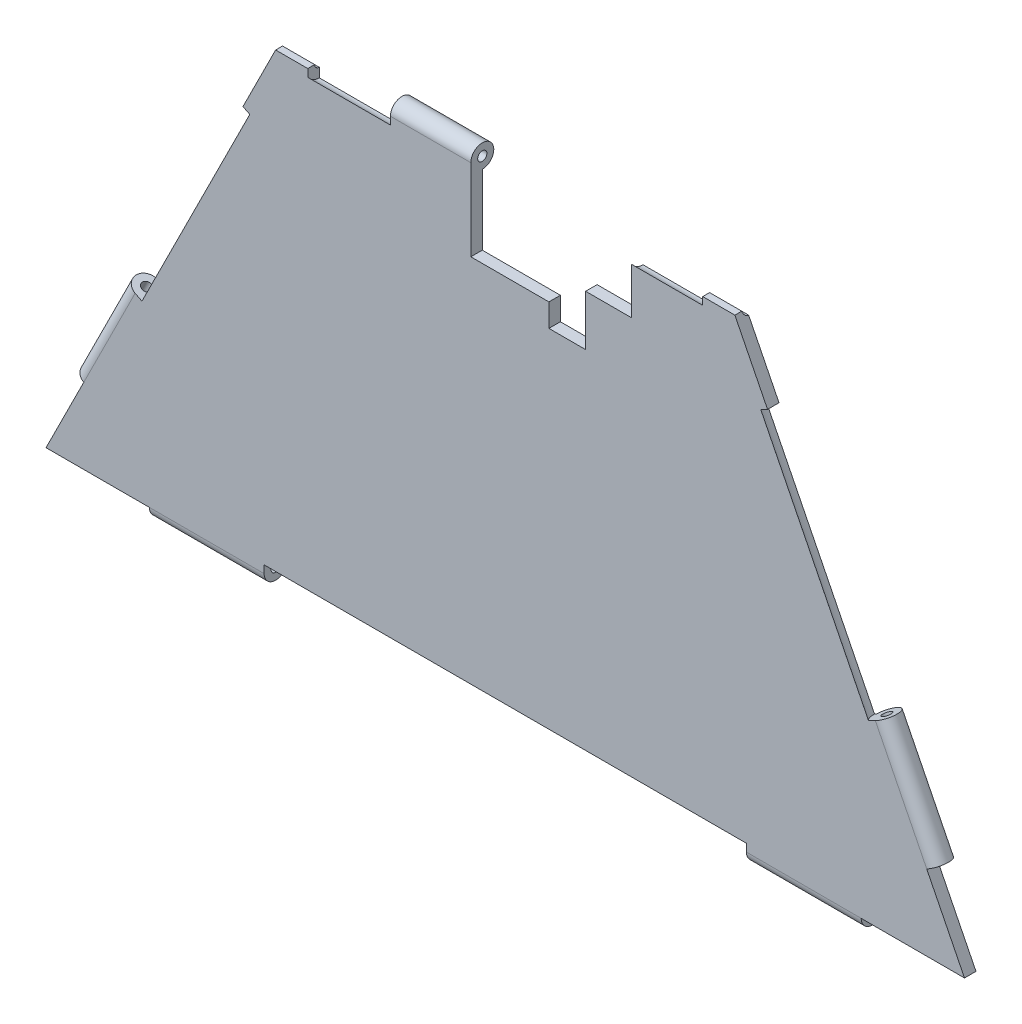
SolidWorks part; units mm, degrees
ref_plane "前视基准面" through (0, 0, 0) normal (0, 0, 1) x (1, 0, 0)
ref_plane "上视基准面" through (0, 0, 0) normal (0, 1, 0) x (1, 0, 0)
ref_plane "右视基准面" through (0, 0, 0) normal (1, 0, 0) x (0, 0, -1)
other "Configuration Table"
sketch "草图1" plane through (0, 0, 0) normal (0, 0, 1) x (1, 0, 0)
  line L0 (-200, 0) -> (-100, 200)
  line L1 (-100, 200) -> (100, 200)
  line L2 (100, 200) -> (200, 0)
  line L3 (200, 0) -> (-200, 0)
  dimension "D1" = 200
  dimension "D2" = 400
  dimension "D3" = 200
extrude "凸台-拉伸1" add sketch "草图1" along normal blind 5
sketch "草图3" plane through (0, 0, 0) normal (0, -1, 0) x (1, 0, 0)
  line L0 (-200, 2.5) -> (200, 2.5) construction
  line L1 (-155, 5) -> (-105, 5)
  line L2 (-155, 5) -> (-155, 0)
  line L3 (-155, 0) -> (-105, 0)
  line L4 (-200, 0) -> (200, 0)
  line L5 (200, 0) -> (200, 5)
  line L6 (200, 5) -> (-200, 5)
  line L7 (-200, 5) -> (-200, 0)
  line L8 (-200, 0) -> (200, 0)
  line L9 (200, 0) -> (200, 5)
  line L10 (200, 5) -> (-200, 5)
  line L11 (-200, 5) -> (-200, 0)
  line L12 (-105, 5) -> (-105, 0)
  line L13 (105, 5) -> (155, 5)
  line L14 (105, 5) -> (105, 0)
  line L15 (105, 0) -> (155, 0)
  line L16 (155, 5) -> (155, 0)
  line L17 (0, 5) -> (0, 0) construction
  dimension "D2" = 50
  dimension "D3" = 210
  dimension "D4" = 5
  dimension "D1" = 0
revolve "旋转5" add sketch "草图3" angle 360 about L3
sketch "草图6" plane through (-160, 80, 0) normal (-0.8944, 0.4472, 0) x (0, 0, 1)
  line L0 (2.5, 134.1641) -> (2.5, -89.4427) construction
  line L1 (5, 134.1641) -> (0, 134.1641) construction
  line L2 (5, -89.4427) -> (0, -89.4427) construction
  line L3 (0, 22.3607) -> (5, 22.3607) construction
  line L4 (0, 134.1641) -> (0, -89.4427) construction
  line L5 (5, 134.1641) -> (5, -89.4427) construction
  line L7 (0, -2.6393) -> (5, -2.6393)
  line L8 (0, -2.6393) -> (0, -52.6393)
  line L9 (0, -52.6393) -> (5, -52.6393)
  line L10 (5, -2.6393) -> (5, -52.6393)
  dimension "D1" = 50
  dimension "D2" = 5
  dimension "D3" = 25
sketch "草图7" plane through (0, 0, 0) normal (0, 0, -1) x (-1, 0, 0)
  line L1 (-50, 200) -> (50, 200)
  line L2 (-50, 200) -> (-50, 195)
  line L3 (-50, 195) -> (50, 195)
  line L4 (50, 200) -> (50, 195)
  line L6 (-100, 200) -> (100, 200) construction
  dimension "D1" = 100
  dimension "D2" = 5
  dimension "D3" = 50
revolve "旋转1" add sketch "草图7" angle 360 about L1
sketch "草图8" plane through (50, 0, 0) normal (1, 0, 0) x (0, 0, -1)
  circle A0 centre (0, 200) radius 2
  dimension "D1" = 4
extrude "切除-拉伸1" cut sketch "草图8" against normal through all both and the other way through all contours A0
revolve "旋转4" add sketch "草图6" angle 360 about L8
sketch "草图9" plane through (-23.541, -47.082, 0) normal (-0.4472, -0.8944, 0) x (0.8944, -0.4472, 0)
  circle A0 centre (-178.8854, 0) radius 2
  dimension "D1" = 4
extrude "切除-拉伸2" cut sketch "草图9" against normal up to surface (50 mm away) up to face at (-161.4891, 77.7937, -0.3452)
sketch "草图10" plane through (-1.1803, -2.3607, 0) normal (0.4472, 0.8944, 0) x (0.8944, -0.4472, 0)
  circle A0 centre (-178.8854, 0) radius 6
  dimension "D1" = 12
extrude "切除-拉伸3" cut sketch "草图10" along normal blind 105
sketch "草图11" plane through (-105, 0, 0) normal (1, 0, 0) x (0, 0, -1)
  circle A0 centre (0, 0) radius 2
  dimension "D1" = 4
extrude "切除-拉伸4" cut sketch "草图11" along normal up to surface and the other way up to surface contours A0 up to face at (155, -0.3452, -0.3452) other way up to face at (-155, -0.3452, -0.3452)
mirror "镜向1" about plane through (0, 0, 0) normal (1, 0, 0) of "切除-拉伸3", "切除-拉伸2", "旋转4"
sketch "草图12" plane through (105, 0, 0) normal (-1, 0, 0) x (0, 0, 1)
  circle A0 centre (0, 0) radius 6
  dimension "D1" = 12
extrude "切除-拉伸5" cut sketch "草图12" along normal up to surface (210 mm away) up to face at (-105, -0.3624, -0.3624)
sketch "草图13" plane through (-50, 0, 0) normal (-1, 0, 0) x (0, 0, 1)
  circle A0 centre (0, 200) radius 6
  arc A1 (5, 200) -> (0, 195) centre (0, 200) ccw construction
  dimension "D1" = 12
extrude "切除-拉伸6" cut sketch "草图13" along normal blind 36
mirror "镜向2" about plane through (0, 0, 0) normal (1, 0, 0) of "切除-拉伸6"
scale "缩放比例1" scale about origin uniform scaling yes scale factor 0.5
sketch "草图18" plane through (0, 0, 2.5) normal (0, 0, 1) x (1, 0, 0)
  line L0 (43, 98.3417) -> (25, 98.3417) construction
  line L1 (27.5, 98.3417) -> (27.5, 88.25)
  line L2 (27.5, 102.1486) -> (27.5, 97.5) construction
  line L3 (27.5, 98.3417) -> (25, 98.3417)
  line L4 (25, 100) -> (25, 98.3417) construction
  line L5 (25, 98.3417) -> (25, 102.5)
  line L6 (25, 102.5) -> (-7.5, 102.5)
  line L8 (-7.5, 82.25) -> (-7.5, 102.5)
  line L9 (-7.5, 82.25) -> (9.5, 82.25)
  line L10 (9.5, 82.25) -> (-7.5, 82.25) construction
  line L11 (9.5, 82.25) -> (9.5, 77.25)
  line L12 (9.5, 77.25) -> (17.5, 77.25)
  line L13 (17.5, 77.25) -> (17.5, 88.25)
  line L14 (17.5, 88.25) -> (27.5, 88.25)
extrude "切除-拉伸8" cut sketch "草图18" against normal blind 10
